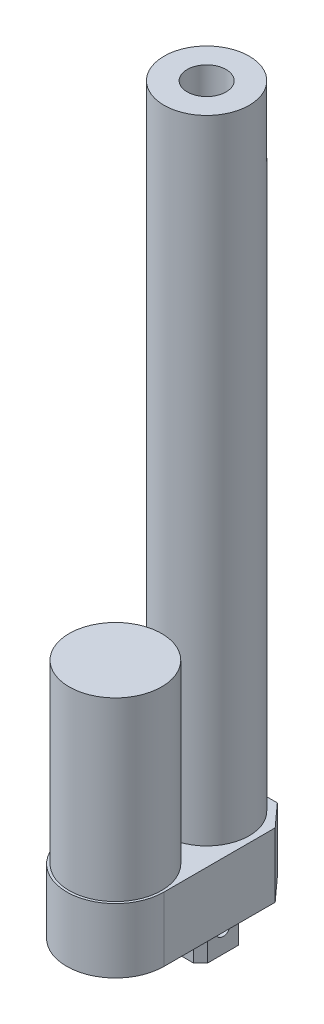
SolidWorks part; units mm, degrees
ref_plane "Front Plane" through (0, 0, 0) normal (0, 0, 1) x (1, 0, 0)
ref_plane "Top Plane" through (0, 0, 0) normal (0, 1, 0) x (1, 0, 0)
ref_plane "Right Plane" through (0, 0, 0) normal (1, 0, 0) x (0, 0, -1)
sketch "Sketch1" plane through (0, 0, 0) normal (0, 1, 0) x (1, 0, 0)
  line L0 (0, -1000) -> (0, 49000) construction
  line L1 (-1000, 0) -> (49000, 0) construction
  line L2 (20, -17.5) -> (20, 28.1704)
  line L3 (11.5432, 37.5) -> (-11.5432, 37.5)
  line L4 (-20, -17.5) -> (-20, 28.1704)
  line L5 (-20, 28.1704) -> (-11.5432, 37.5)
  line L6 (20, 28.1704) -> (11.5432, 37.5)
  arc A0 (-20, -17.5) -> (20, -17.5) centre (0, -17.5) ccw
  point P0 (0, 0)
  dimension "D3" = 40
  dimension "D1" = 20
  dimension "D2" = 37.5
extrude "Boss-Extrude1" add sketch "Sketch1" along normal blind 26.5
sketch "Sketch2" plane through (0, 26.5, 0) normal (0, 1, 0) x (1, 0, 0)
  circle A0 centre (0, -17.5) radius 19
  dimension "D1" = 38
extrude "Boss-Extrude2" add sketch "Sketch2" along normal blind 72.5
sketch "Sketch3" plane through (0, 0, 0) normal (0, -1, 0) x (1, 0, 0)
  line L0 (11.5432, -37.5) -> (-11.5432, -37.5) construction
  line L1 (6.3703, -26.75) -> (-6.3703, -26.75)
  line L2 (9.25, -23.8703) -> (9.25, -11.1297)
  line L3 (6.3703, -8.25) -> (-6.3703, -8.25)
  line L4 (-9.25, -23.8703) -> (-9.25, -11.1297)
  line L7 (20, 17.5) -> (20, -28.1704) construction
  line L9 (-6.3703, -8.25) -> (-9.25, -11.1297)
  line L10 (-9.25, -23.8703) -> (-6.3703, -26.75)
  line L11 (6.3703, -26.75) -> (9.25, -23.8703)
  line L12 (9.25, -11.1297) -> (6.3703, -8.25)
  point P0 (0, -17.5)
  dimension "D3" = 20
  dimension "D4" = 20
extrude "Boss-Extrude3" add sketch "Sketch3" along normal blind 18.5
sketch "Sketch4" plane through (9.25, 0, 0) normal (1, 0, 0) x (0, 0, -1)
  line L0 (23.8703, -18.5) -> (11.1297, -18.5) construction
  line L1 (11.1297, -18.5) -> (11.1297, 0) construction
  circle A0 centre (17.5, -9.25) radius 3
  point P5 (17.5, -18.5)
  point P9 (11.1297, -9.25)
  dimension "D1" = 6
extrude "Cut-Extrude1" cut sketch "Sketch4" against normal blind 18.5
sketch "Sketch5" plane through (0, 26.5, 0) normal (0, 1, 0) x (1, 0, 0)
  line L0 (11.5432, 37.5) -> (-11.5432, 37.5) construction
  circle A0 centre (0, 20) radius 17.5
  dimension "D1" = 35
extrude "Boss-Extrude4" add sketch "Sketch5" along normal blind 260
sketch "Sketch6" plane through (0, 286.5, 0) normal (0, 1, 0) x (1, 0, 0)
  circle A0 centre (0, 20) radius 8
  dimension "D1" = 16
extrude "Cut-Extrude2" cut sketch "Sketch6" against normal blind 200
